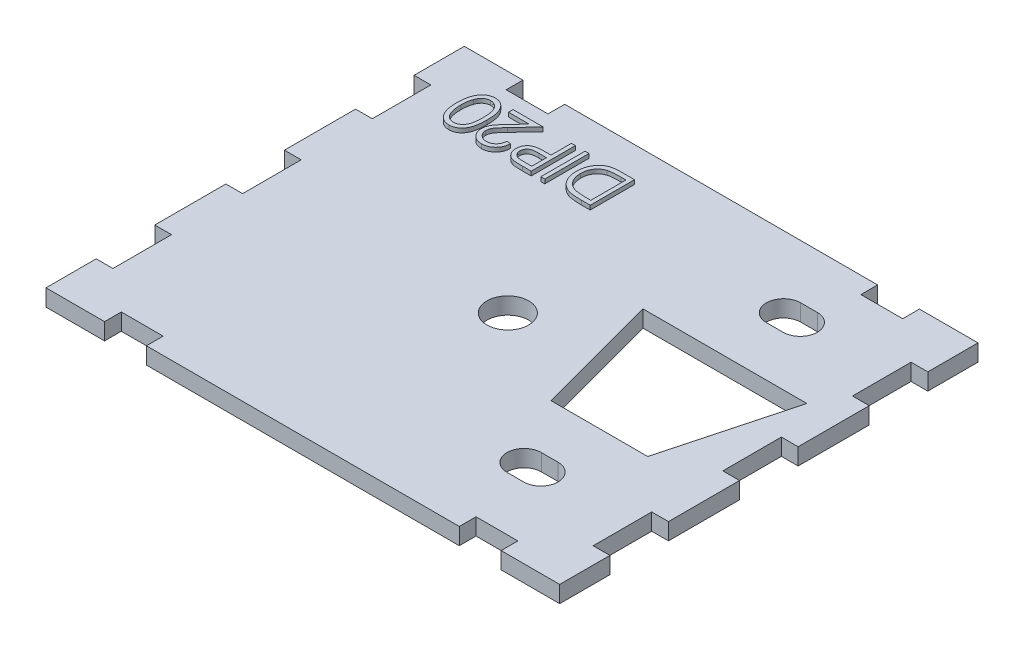
SolidWorks part; units mm, degrees
ref_plane "Front Plane" through (0, 0, 0) normal (0, 0, 1) x (1, 0, 0)
ref_plane "Top Plane" through (0, 0, 0) normal (0, 1, 0) x (1, 0, 0)
ref_plane "Right Plane" through (0, 0, 0) normal (1, 0, 0) x (0, 0, -1)
sketch "Sketch2" plane through (0, 0, 0) normal (0, 1, 0) x (1, 0, 0)
  line L1 (-50, 25) -> (50, 25)
  line L2 (-50, 25) -> (-50, -25)
  line L3 (-50, -25) -> (50, -25)
  line L4 (50, 25) -> (50, -25)
  line L5 (-50, 25) -> (50, -25) construction
  line L6 (-50, -25) -> (50, 25) construction
  point P0 (0, 0)
  dimension "D1" = 100
  dimension "D2" = 50
extrude "Boss-Extrude1" add sketch "Sketch2" along normal blind 2
sketch "Sketch12" plane through (0, 2, 0) normal (0, 1, 0) x (1, 0, 0)
  line L0 (-50, -25) -> (50, -25) construction
  line L1 (-40.2, -25) -> (-50, -25)
  line L2 (-40.2, -25) -> (-40.2, 25)
  line L3 (-40.2, 25) -> (-50, 25)
  line L4 (-50, -25) -> (-50, 25)
  line L5 (-50, -25) -> (50, -25) construction
  line L6 (41.2, -25) -> (50, -25)
  line L7 (41.2, -25) -> (41.2, 25)
  line L8 (41.2, 25) -> (50, 25)
  line L9 (50, -25) -> (50, 25)
extrude "Cut-Extrude8" cut sketch "Sketch12" against normal blind 6
sketch "Sketch13" plane through (0, 2, 0) normal (0, 1, 0) x (1, 0, 0)
  line L1 (-28.2, 19) -> (-30.2, 19)
  line L2 (-28.2, 19) -> (-28.2, 12)
  line L3 (-28.2, 12) -> (-30.2, 12)
  line L4 (-30.2, 19) -> (-30.2, 12)
  line L5 (-28.2, 3.5) -> (-30.2, 3.5)
  line L6 (-28.2, 3.5) -> (-28.2, -3.5)
  line L7 (-28.2, -3.5) -> (-30.2, -3.5)
  line L8 (-30.2, 3.5) -> (-30.2, -3.5)
  line L9 (-28.2, -12) -> (-30.2, -12)
  line L10 (-28.2, -12) -> (-28.2, -19)
  line L11 (-28.2, -19) -> (-30.2, -19)
  line L12 (-30.2, -12) -> (-30.2, -19)
  line L13 (29.2, 19) -> (31.2, 19)
  line L14 (29.2, 19) -> (29.2, 12)
  line L15 (29.2, 12) -> (31.2, 12)
  line L16 (31.2, 19) -> (31.2, 12)
  line L17 (29.2, 3.5) -> (31.2, 3.5)
  line L18 (29.2, 3.5) -> (29.2, -3.5)
  line L19 (29.2, -3.5) -> (31.2, -3.5)
  line L20 (31.2, 3.5) -> (31.2, -3.5)
  line L21 (29.2, -12) -> (31.2, -12)
  line L22 (29.2, -12) -> (29.2, -19)
  line L23 (29.2, -19) -> (31.2, -19)
  line L24 (31.2, -12) -> (31.2, -19)
  line L25 (-40.2, -25) -> (41.2, -25) construction
  line L26 (-23.2, 25) -> (-18.2, 25)
  line L27 (41.2, 25) -> (-40.2, 25) construction
  line L28 (-40.2, -25) -> (41.2, -25) construction
  line L29 (41.2, 25) -> (-40.2, 25) construction
  line L30 (-40.2, -25) -> (41.2, -25) construction
  line L31 (41.2, 25) -> (31.2, 25)
  line L32 (41.2, 25) -> (41.2, -25)
  line L33 (41.2, -25) -> (31.2, -25)
  line L34 (31.2, 25) -> (31.2, -25)
  line L35 (41.2, 25) -> (-40.2, 25) construction
  line L36 (-40.2, -25) -> (-30.2, -25)
  line L37 (-40.2, -25) -> (-40.2, 25)
  line L38 (-40.2, 25) -> (-30.2, 25)
  line L39 (-30.2, -25) -> (-30.2, 25)
  line L40 (-23.2, 25) -> (-23.2, 23)
  line L41 (-23.2, 23) -> (-18.2, 23)
  line L42 (-18.2, 25) -> (-18.2, 23)
  line L43 (-23.2, -25) -> (-18.2, -25)
  line L44 (-23.2, -25) -> (-23.2, -23)
  line L45 (-23.2, -23) -> (-18.2, -23)
  line L46 (-18.2, -25) -> (-18.2, -23)
  line L47 (24.2, -25) -> (19.2, -25)
  line L48 (24.2, -25) -> (24.2, -23)
  line L49 (24.2, -23) -> (19.2, -23)
  line L50 (19.2, -25) -> (19.2, -23)
  line L51 (24.2, 25) -> (19.2, 25)
  line L52 (24.2, 25) -> (24.2, 23)
  line L53 (24.2, 23) -> (19.2, 23)
  line L54 (19.2, 25) -> (19.2, 23)
  point P24 (29.2, 0)
  point P30 (30.2, 3.5)
  line M32 (41.2, -25) -> (41.2, 25)
  line M41 (41.2, 25) -> (-40.2, 25)
  line M42 (-40.2, 25) -> (-40.2, -25)
  line M47 (-40.2, -25) -> (41.2, -25)
  dimension "D1" = 2
  dimension "D2" = 2
  dimension "D3" = 2
  dimension "D4" = 2
  dimension "D5" = 2
  dimension "D6" = 2
  dimension "D7" = 57.4
  dimension "D8" = 57.4
  dimension "D9" = 57.4
  dimension "D10" = 7
  dimension "D11" = 7
  dimension "D12" = 7
  dimension "D13" = 7
  dimension "D14" = 7
  dimension "D15" = 7
  dimension "D16" = 5
  dimension "D17" = 2
  dimension "D18" = 5
  dimension "D19" = 6
  dimension "D20" = 8.5
  dimension "D21" = 8.5
  dimension "D22" = 6
  dimension "D23" = 6
  dimension "D24" = 8.5
  dimension "D25" = 8.5
  dimension "D26" = 6
  dimension "D27" = 5
  dimension "D28" = 5
  dimension "D29" = 2
  dimension "D30" = 2
  dimension "D31" = 5
  dimension "D32" = 5
  dimension "D33" = 5
  dimension "D34" = 5
  dimension "D35" = 2
extrude "Cut-Extrude10" cut sketch "Sketch13" against normal blind 6 contours L5 L8 L7 L6 | L39 L12 L8 L4 M47 M41 M42 | L1 L4 L3 L2 | L50 L48 L49 M47 | L24 L21 L22 L23 | L20 L17 L18 L19 | L16 L13 L14 L15 | L54 L53 L52 M41 | L9 L12 L11 L10 | L34 L16 L20 L24 M41 M47 M32 | L26 L42 L41 L40 | L45 L46 L43 L44
sketch "Sketch15" plane through (0, 0, 0) normal (0, -1, 0) x (1, 0, 0)
  line L0 (24.2, 23) -> (19.2, 23) construction
  line L16 (20.7242, -7.5) -> (20.7242, -8.5)
  line L17 (20.7242, -7.5) -> (25.936, -7.5)
  line L18 (25.936, -7.5) -> (22.4527, 5.5)
  line L19 (22.4527, 5.5) -> (12.4527, 5.5)
  line L20 (12.4527, 5.5) -> (8.9693, -7.5)
  line L21 (8.9693, -7.5) -> (14.1811, -7.5)
  line L22 (14.1811, -7.5) -> (14.1811, -8.5)
  line L23 (14.1811, -8.5) -> (7.6661, -8.5)
  line L24 (7.6661, -8.5) -> (11.6853, 6.5)
  line L25 (11.6853, 6.5) -> (23.22, 6.5)
  line L26 (23.22, 6.5) -> (27.2392, -8.5)
  line L27 (27.2392, -8.5) -> (20.7242, -8.5)
  line L28 (20.7242, -8.5) -> (14.1811, -8.5)
  line L29 (14.1811, -7.5) -> (20.7242, -7.5)
  line L31 (29.2, 12) -> (29.2, 19) construction
  dimension "D4" = 16.5
  dimension "D18" = 11.5347
  dimension "D19" = 15.5291
  dimension "D20" = 15.5291
  dimension "D21" = 13.4586
  dimension "D22" = 13.4586
  dimension "D23" = 10
  dimension "D24" = 5.2118
  dimension "D25" = 5.2118
  dimension "D26" = 6.515
  dimension "D27" = 6.515
  dimension "D28" = 1
  dimension "D29" = 105
  dimension "D30" = 105
  dimension "D31" = 75
  dimension "D32" = 75
  dimension "D33" = 5.98
  dimension "D34" = 1
extrude "Cut-Extrude13" cut sketch "Sketch15" against normal blind 10 contours L21 L29 L17 L18 L19 L20 | L27 L26 L25 L24 L23 L22 L21 L20 L19 L18 L17 L16 | L29 L22 L28 L16
sketch "Sketch16" plane through (0, 0, 0) normal (0, -1, 0) x (-1, 0, 0)
  circle A0 centre (0, 0) radius 2.5
  dimension "D1" = 5
extrude "Cut-Extrude14" cut sketch "Sketch16" against normal blind 10 contours A0
sketch "Sketch17" plane through (0, 0, 0) normal (0, -1, 0) x (-1, 0, 0)
  line L0 (-18.4527, -16.55) -> (-16.4527, -16.55)
  line L1 (-16.4527, -12.45) -> (-18.4527, -12.45)
  line L2 (-27.2392, 8.5) -> (-7.6661, 8.5) construction
  line L3 (-18.4527, 14.45) -> (-16.4527, 14.45)
  line L4 (-11.6853, -6.5) -> (-23.22, -6.5) construction
  line L5 (-18.4527, 18.55) -> (-16.4527, 18.55)
  circle A0 centre (-17.4527, -14.5) radius 2.05
  circle A1 centre (-17.4527, 16.5) radius 2.05
  circle A2 centre (-16.4527, 16.5) radius 2.05
  circle A3 centre (-18.4527, 16.5) radius 2.05
  circle A4 centre (-16.4527, -14.5) radius 2.05
  circle A5 centre (-18.4527, -14.5) radius 2.05
  dimension "D1" = 4.1
  dimension "D2" = 4.1
  dimension "D9" = 1
  dimension "D3" = 8
  dimension "D4" = 9.7866
  dimension "D5" = 9.7866
  dimension "D6" = 5.7673
  dimension "D7" = 5.7673
  dimension "D8" = 8
  dimension "D10" = 0
  dimension "D11" = 1
  dimension "D12" = 0
  dimension "D13" = 1
  dimension "D14" = 0
  dimension "D15" = 1
  dimension "D16" = 0
extrude "Cut-Extrude15" cut sketch "Sketch17" against normal blind 3.5 contours A3 A1 L5 | A3 A2 A1 | A2 L5 A1 | A2 A1 | A3 A2 A1 | A2 A3 | A1 A3 A2 | A3 A1 | A3 L3 A1 | A3 A1 A2 | A2 A1 L3 | A5 A0 L1 | A5 A4 A0 | A4 L1 A0 | A4 A0 | A5 A4 A0 | A4 A5 | A0 A5 A4 | A5 A0 | A5 A0 A4 | A4 A0 L0 | A5 L0 A0
sketch "Sketch22" plane through (0, 2, 0) normal (0, 1, 0) x (1, 0, 0)
  line L0 (-24.5837, 20.8621) -> (9.284, 20.8621) construction
  text T0 "DIP20" font "Century Gothic" height in points 20
extrude "Boss-Extrude4" add sketch "Sketch22" along normal blind 0.5
